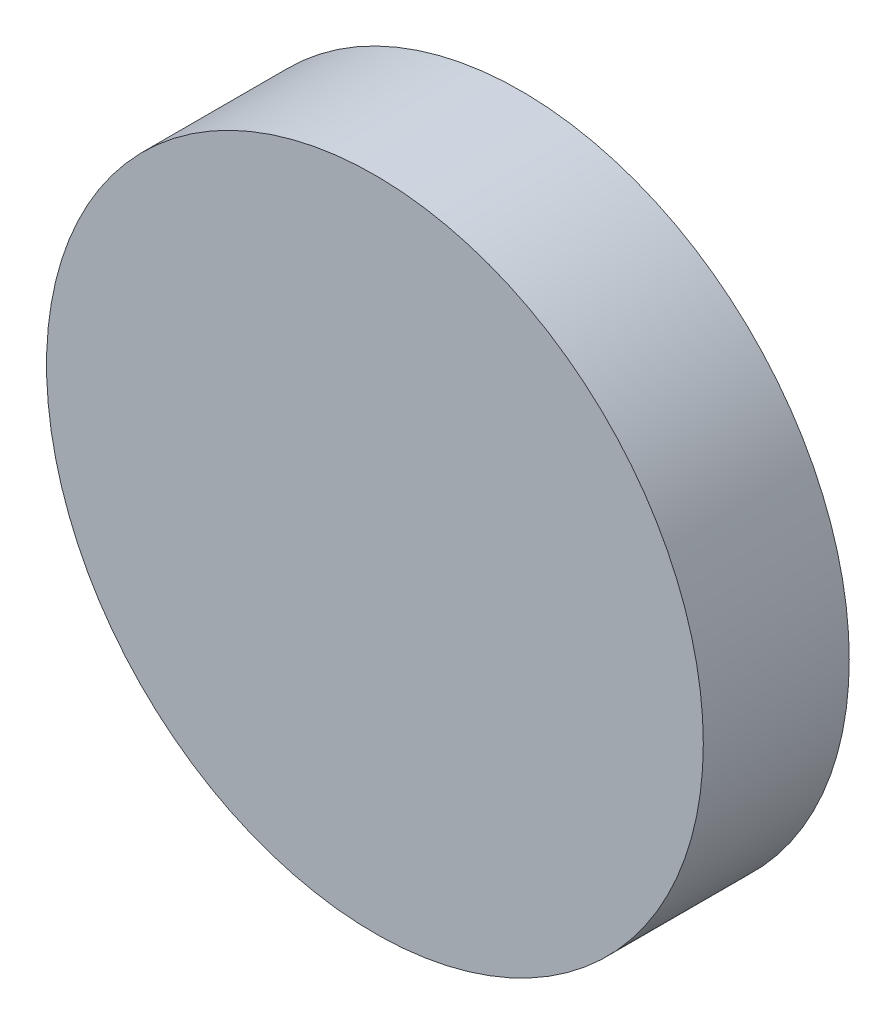
SolidWorks part; units mm, degrees
ref_plane "Front Plane" through (0, 0, 0) normal (0, 0, 1) x (1, 0, 0)
ref_plane "Top Plane" through (0, 0, 0) normal (0, 1, 0) x (1, 0, 0)
ref_plane "Right Plane" through (0, 0, 0) normal (1, 0, 0) x (0, 0, -1)
other "Configuration Table"
sketch "Sketch1" plane through (0, 0, 0) normal (0, 0, 1) x (1, 0, 0)
  circle A0 centre (700, 550) radius 90
extrude "STORE_evap_fan_2" add sketch "Sketch1" against normal blind 40 from offset 750 separate body
